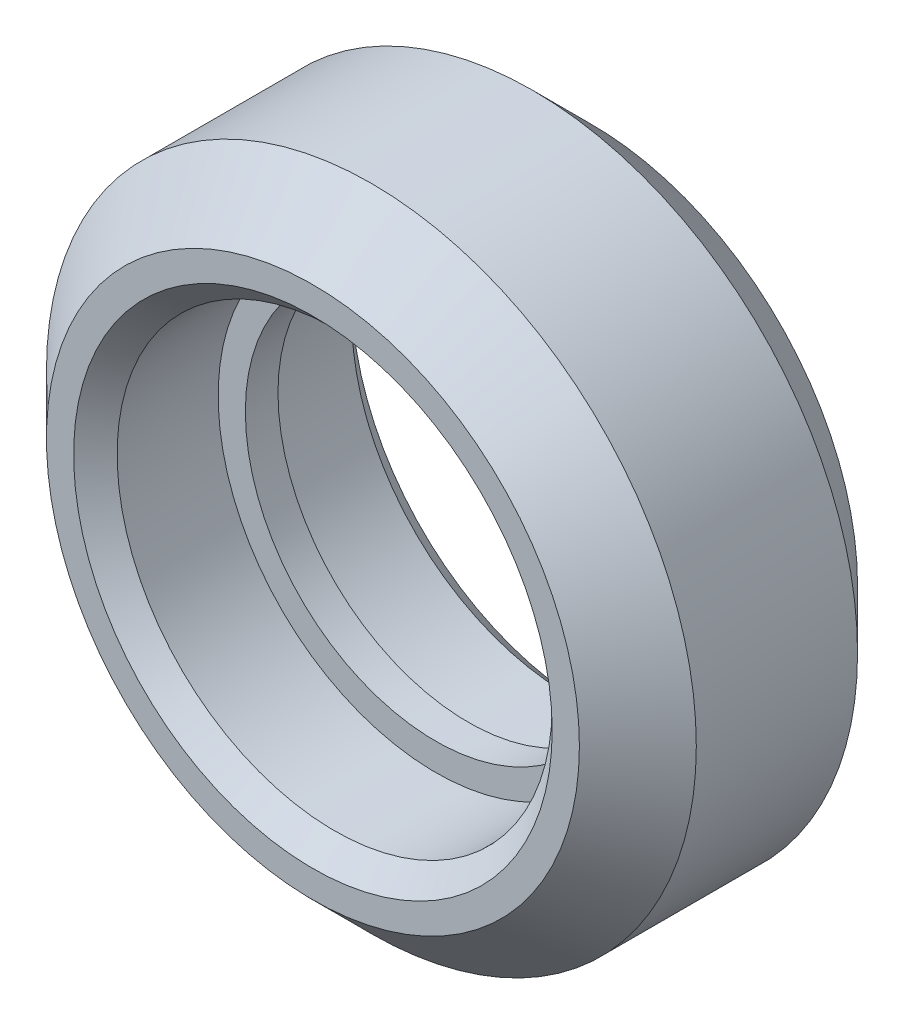
SolidWorks part; units mm, degrees
material "PA Тип 6"
ref_plane "Спереди" through (0, 0, 0) normal (0, 0, 1) x (1, 0, 0)
ref_plane "Сверху" through (0, 0, 0) normal (0, 1, 0) x (1, 0, 0)
ref_plane "Справа" through (0, 0, 0) normal (1, 0, 0) x (0, 0, -1)
sketch "Эскиз1" plane through (0, 0, 0) normal (0, 0, 1) x (1, 0, 0)
  circle A0 centre (0, 0) radius 11.95
  dimension "D1" = 23.9
extrude "Бобышка-Вытянуть1" add sketch "Эскиз1" along normal blind 10.23
sketch "Эскиз2" plane through (0, 0, 10.23) normal (0, 0, 1) x (1, 0, 0)
  circle A0 centre (0, 0) radius 7
  dimension "D1" = 14
extrude "Вырез-Вытянуть1" cut sketch "Эскиз2" against normal through all
chamfer "Фаска1" distance 2.15 angle 45 2 edges at (11.95, 0, 0) (11.95, 0, 10.23)
ref_plane "Плоскость1" through (0, 0, 5.115) normal (0, 0, -1) x (-1, 0, 0)
sketch "Эскиз3" plane through (0, 0, 10.23) normal (0, 0, 1) x (1, 0, 0)
  circle A0 centre (0, 0) radius 8
  dimension "D1" = 16
extrude "Вырез-Вытянуть2" cut sketch "Эскиз3" against normal blind 4.515
mirror "Зеркальное отражение1" about plane through (0, 0, 5.115) normal (0, 0, -1) of "Вырез-Вытянуть2"
chamfer "Фаска2" distance 0.8 angle 45 2 edges at (8, 0, 0) (8, 0, 10.23)
